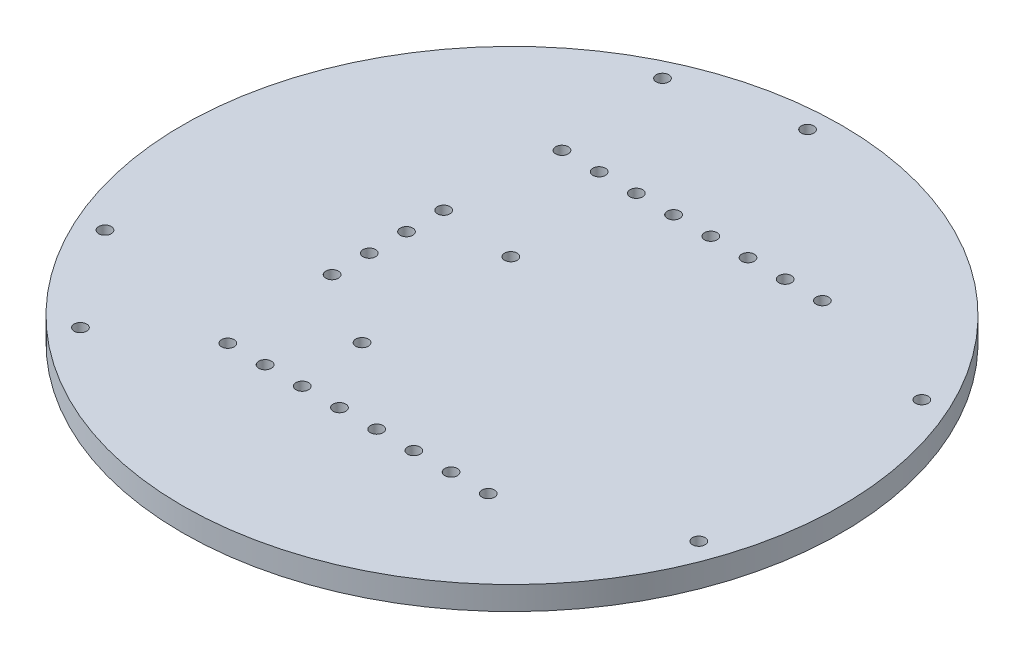
SolidWorks part; units mm, degrees
ref_plane "Front Plane" through (0, 0, 0) normal (0, 0, 1) x (1, 0, 0)
ref_plane "Top Plane" through (0, 0, 0) normal (0, 1, 0) x (1, 0, 0)
ref_plane "Right Plane" through (0, 0, 0) normal (1, 0, 0) x (0, 0, -1)
sketch "Sketch1" plane through (0, 0, 0) normal (0, 1, 0) x (1, 0, 0)
  circle A1 centre (0, 0) radius 22.5
  dimension "D1" = 45
extrude "Boss-Extrude1" add sketch "Sketch1" along normal blind 1.6 contours A1
sketch "Sketch2" plane through (0, 0, 0) normal (0, -1, 0) x (1, 0, 0)
  circle A0 centre (9.721, 11.3406) radius 0.4292
  circle A1 centre (7.181, 11.3406) radius 0.4292
  circle A2 centre (4.641, 11.3406) radius 0.4292
  circle A3 centre (2.101, 11.3406) radius 0.4292
  circle A4 centre (-0.439, 11.3406) radius 0.4292
  circle A5 centre (-2.979, 11.3406) radius 0.4292
  circle A6 centre (-5.519, 11.3406) radius 0.4292
  circle A7 centre (-8.059, 11.3406) radius 0.4292
  circle A8 centre (9.721, -11.47) radius 0.4292
  circle A9 centre (7.181, -11.47) radius 0.4292
  circle A10 centre (4.641, -11.47) radius 0.4292
  circle A11 centre (2.101, -11.47) radius 0.4292
  circle A12 centre (-0.439, -11.47) radius 0.4292
  circle A13 centre (-2.979, -11.47) radius 0.4292
  circle A14 centre (-5.519, -11.47) radius 0.4292
  circle A15 centre (-8.059, -11.47) radius 0.4292
  circle A17 centre (-8.5549, 3.7283) radius 0.4292
  circle A18 centre (-8.5549, 1.1883) radius 0.4292
  circle A19 centre (-8.5549, -1.3517) radius 0.4292
  circle A20 centre (-8.5549, -3.8917) radius 0.4292
  circle A21 centre (-3.5138, 6.7263) radius 0.4292
  circle A22 centre (-14.0139, 15.4511) radius 0.4292
  circle A23 centre (-18.9407, 8.8475) radius 0.4292
  circle A24 centre (-3.5138, -3.4366) radius 0.4292
  circle A25 centre (-8.8841, -19.158) radius 0.4292
  circle A26 centre (-0.9069, -21.0889) radius 0.4292
  circle A27 centre (19.7228, 6.9705) radius 0.4292
  circle A28 centre (18.9718, -9.0095) radius 0.4292
  point P42 (-3.5138, 6.7263)
  point P45 (-14.0139, 15.4511)
  point P48 (-18.9407, 8.8475)
  point P51 (-3.5138, -3.4366)
  point P54 (-8.8841, -19.158)
  point P57 (-0.9069, -21.0889)
  point P60 (19.8907, 6.7263)
  point P63 (18.969, -8.9034)
  point P64 (19.7228, 6.9705)
  point P65 (18.9718, -9.0095)
  dimension "D1" = 8
  dimension "D2" = 4
extrude "Cut-Extrude1" cut sketch "Sketch2" against normal through all
